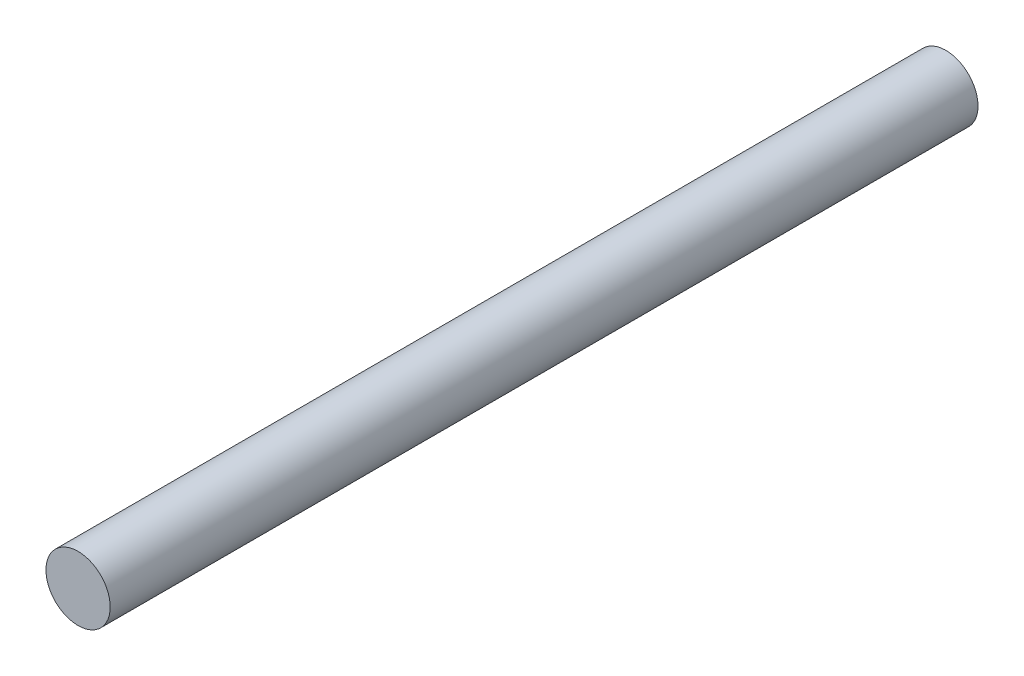
SolidWorks part; units mm, degrees
material "Acero al carbono no aleado"
ref_plane "Alzado" through (0, 0, 0) normal (0, 0, 1) x (1, 0, 0)
ref_plane "Planta" through (0, 0, 0) normal (0, 1, 0) x (1, 0, 0)
ref_plane "Vista lateral" through (0, 0, 0) normal (1, 0, 0) x (0, 0, -1)
sketch "Croquis1" plane through (0, 0, 0) normal (0, 0, 1) x (1, 0, 0)
  circle A0 centre (0, 0) radius 10
  dimension "D1" = 20
extrude "Saliente-Extruir1" add sketch "Croquis1" along normal blind 270
